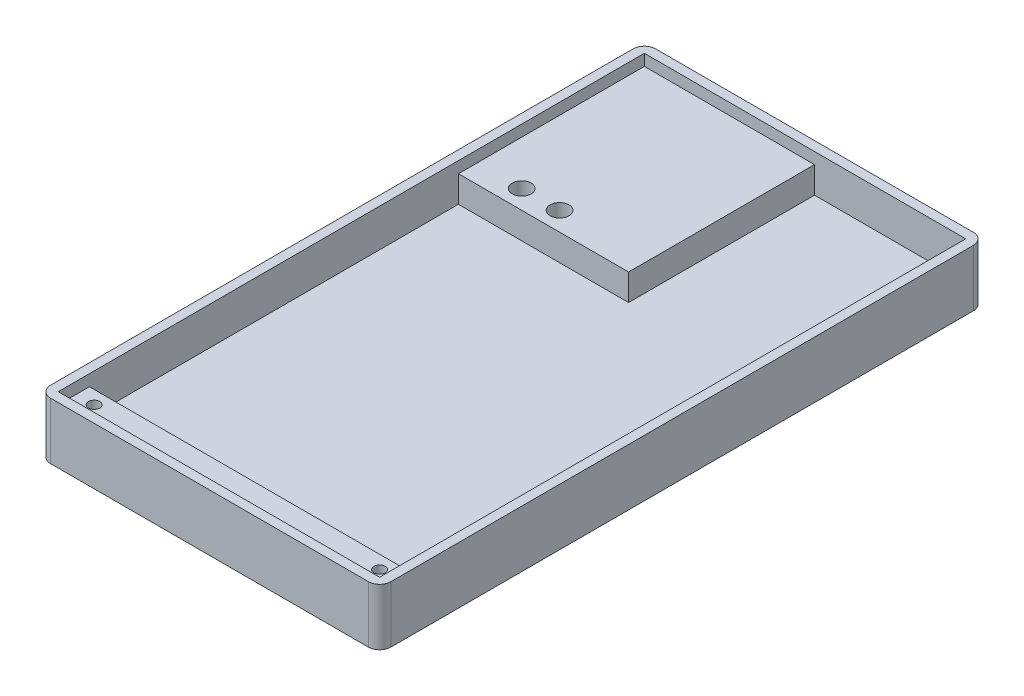
SolidWorks part; units mm, degrees
ref_plane "Front Plane" through (0, 0, 0) normal (0, 0, 1) x (1, 0, 0)
ref_plane "Top Plane" through (0, 0, 0) normal (0, 1, 0) x (1, 0, 0)
ref_plane "Right Plane" through (0, 0, 0) normal (1, 0, 0) x (0, 0, -1)
sketch "Sketch1" plane through (0, 0, 0) normal (0, 1, 0) x (1, 0, 0)
  line L1 (-43.2731, 51.8059) -> (46.7269, 51.8059)
  line L2 (-43.2731, 51.8059) -> (-43.2731, -108.1941)
  line L3 (-43.2731, -108.1941) -> (46.7269, -108.1941)
  line L4 (46.7269, 51.8059) -> (46.7269, -108.1941)
  dimension "D1" = 90
  dimension "D2" = 160
extrude "Boss-Extrude1" add sketch "Sketch1" along normal blind 5 contours L1 L4 L3 L2
sketch "Sketch2" plane through (0, 5, 0) normal (0, 1, 0) x (1, 0, 0)
  line L1 (-43.2731, 51.8059) -> (46.7269, 51.8059)
  line L2 (-43.2731, 51.8059) -> (-43.2731, -108.1941)
  line L3 (-43.2731, -108.1941) -> (46.7269, -108.1941)
  line L4 (46.7269, 51.8059) -> (46.7269, -108.1941)
  line L5 (-40.7731, 49.3059) -> (44.2269, 49.3059)
  line L6 (-40.7731, 49.3059) -> (-40.7731, -105.6941)
  line L7 (-40.7731, -105.6941) -> (44.2269, -105.6941)
  line L8 (44.2269, 49.3059) -> (44.2269, -105.6941)
  dimension "D1" = 85
  dimension "D2" = 2.5
  dimension "D3" = 155
  dimension "D4" = 2.5
extrude "Boss-Extrude2" add sketch "Sketch2" along normal blind 10
sketch "Sketch3" plane through (0, 5, 0) normal (0, 1, 0) x (1, 0, 0)
  line L0 (44.2269, -105.6941) -> (44.2269, 49.3059) construction
  line L1 (-40.7731, -105.6941) -> (44.2269, -105.6941)
  line L2 (-40.7731, -105.6941) -> (-40.7731, -97.4441)
  line L3 (-40.7731, -97.4441) -> (44.2269, -97.4441)
  line L4 (44.2269, -105.6941) -> (44.2269, -97.4441)
  circle A0 centre (-36.0231, -100.9441) radius 1.5
  circle A1 centre (39.4769, -100.9441) radius 1.5
  point P13 (-29.9962, -77.8679)
  dimension "D4" = 3
  dimension "D7" = 3
  dimension "D1" = 8.25
  dimension "D2" = 4.75
  dimension "D3" = 4.75
  dimension "D5" = 4.75
  dimension "D6" = 4.75
extrude "Boss-Extrude3" add sketch "Sketch3" along normal blind 7
sketch "Sketch4" plane through (0, 5, 0) normal (0, 1, 0) x (1, 0, 0)
  line L0 (-40.7731, 49.3059) -> (-40.7731, -97.4441) construction
  line L1 (-40.7731, 10.1309) -> (4.2269, 10.1309)
  line L2 (-40.7731, 10.1309) -> (-40.7731, 0.1309)
  line L3 (-40.7731, 0.1309) -> (4.2269, 0.1309)
  line L4 (4.2269, 10.1309) -> (4.2269, 0.1309)
  line L5 (44.2269, 49.3059) -> (-40.7731, 49.3059) construction
  line L7 (4.2269, 10.1309) -> (-40.7731, 10.1309)
  line L8 (4.2269, 10.1309) -> (4.2269, 49.3059)
  line L9 (4.2269, 49.3059) -> (-40.7731, 49.3059)
  line L10 (-40.7731, 10.1309) -> (-40.7731, 49.3059)
  circle A0 centre (-29.0231, 5.1309) radius 2.5
  circle A1 centre (-19.0231, 5.1309) radius 2.5
  line M6 (-40.7731, 49.3059) -> (-40.7731, -97.4441)
  line M9 (44.2269, 49.3059) -> (-40.7731, 49.3059)
  dimension "D3" = 5
  dimension "D4" = 5
  dimension "D1" = 11.75
  dimension "D2" = 21.75
  dimension "D5" = 10
  dimension "D6" = 5
  dimension "D7" = 5
  dimension "D8" = 44.175
  dimension "D9" = 45
extrude "Boss-Extrude4" add sketch "Sketch4" along normal up to surface (7 mm away) contours L1 L8 M9 M6 | L4 L1 L3 A1 A0 M6 up to face at (1.7269, 12, 101.5691)
fillet "Fillet1" radius 3 4 edges at (-43.2731, 7.5, -51.8059) (46.7269, 7.5, -51.8059) (46.7269, 7.5, 108.1941) (-43.2731, 7.5, 108.1941)
sketch "Sketch5" plane through (0, 5, 0) normal (0, 1, 0) x (1, 0, 0)
  circle A0 centre (-19.0231, 5.1309) radius 2.5
  circle A1 centre (-29.0231, 5.1309) radius 2.5593
  circle A2 centre (-36.0231, -100.9441) radius 1.5
  circle A3 centre (39.4769, -100.9441) radius 1.5
extrude "Cut-Extrude1" cut sketch "Sketch5" against normal through all
